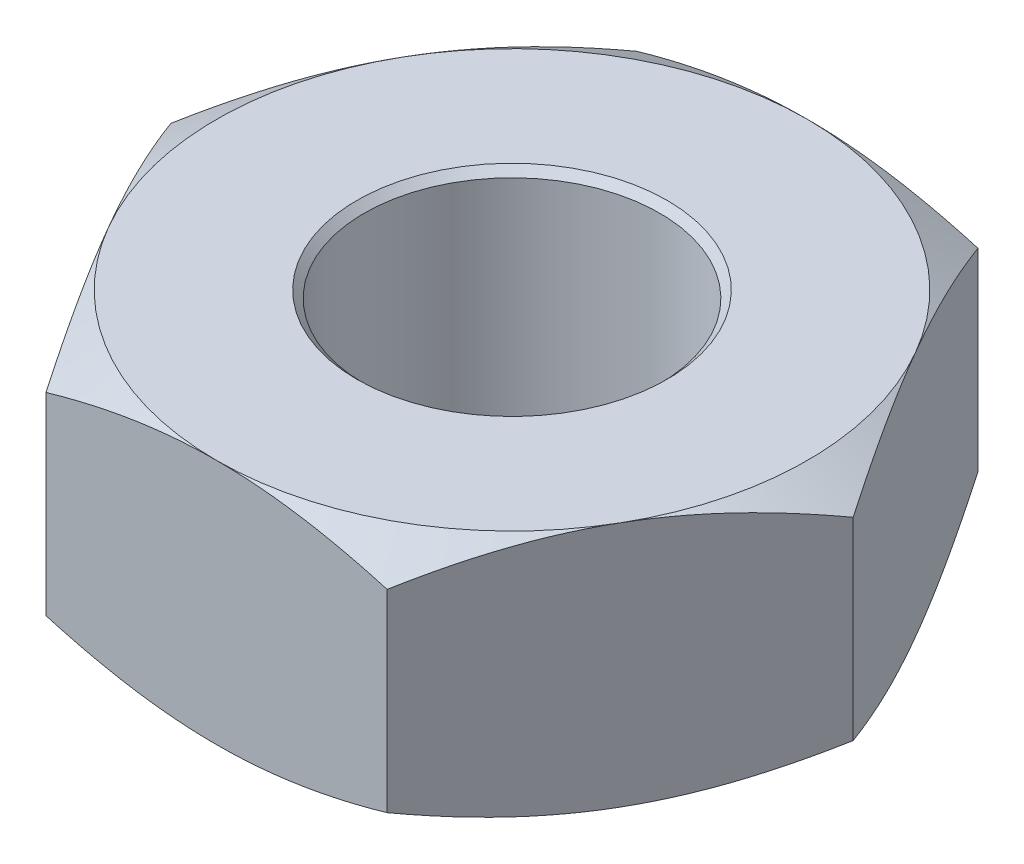
SolidWorks part; units mm, degrees
ref_plane "Front Plane" through (0, 0, 0) normal (0, 0, 1) x (1, 0, 0)
ref_plane "Top Plane" through (0, 0, 0) normal (0, 1, 0) x (1, 0, 0)
ref_plane "Right Plane" through (0, 0, 0) normal (1, 0, 0) x (0, 0, -1)
sketch "Sketch2" plane through (0, 0, 0) normal (0, 1, 0) x (1, 0, 0)
  line L1 (3.4641, 0) -> (1.7321, 3)
  line L2 (1.7321, 3) -> (-1.7321, 3)
  line L3 (-1.7321, 3) -> (-3.4641, 0)
  line L4 (-3.4641, 0) -> (-1.7321, -3)
  line L5 (-1.7321, -3) -> (1.7321, -3)
  line L6 (1.7321, -3) -> (3.4641, 0)
  circle A0 centre (0, 0) radius 1.5
  circle A1 centre (0, 0) radius 3 construction
  dimension "D1" = 3
  dimension "D2" = 6
extrude "Boss-Extrude1" add sketch "Sketch2" along normal blind 2.5
sketch "Sketch3" plane through (0, 0, 0) normal (0, 1, 0) x (1, 0, 0)
  circle A0 centre (0, 0) radius 3 construction
  circle A1 centre (0, 0) radius 3
extrude "Cut-Extrude1" cut sketch "Sketch3" along normal blind 3.25 draft 60 flip side to cut
sketch "Sketch4" plane through (0, 2.5, 0) normal (0, 1, 0) x (1, 0, 0)
  circle A1 centre (0, 0) radius 3
  circle A2 centre (0, 0) radius 3
  dimension "D1" = 0
extrude "Cut-Extrude2" cut sketch "Sketch4" against normal blind 3.25 draft 60 flip side to cut
chamfer "Chamfer1" distance 0.075 angle 45 2 edges at (0, 0, 1.5) (0, 2.5, 1.5)
